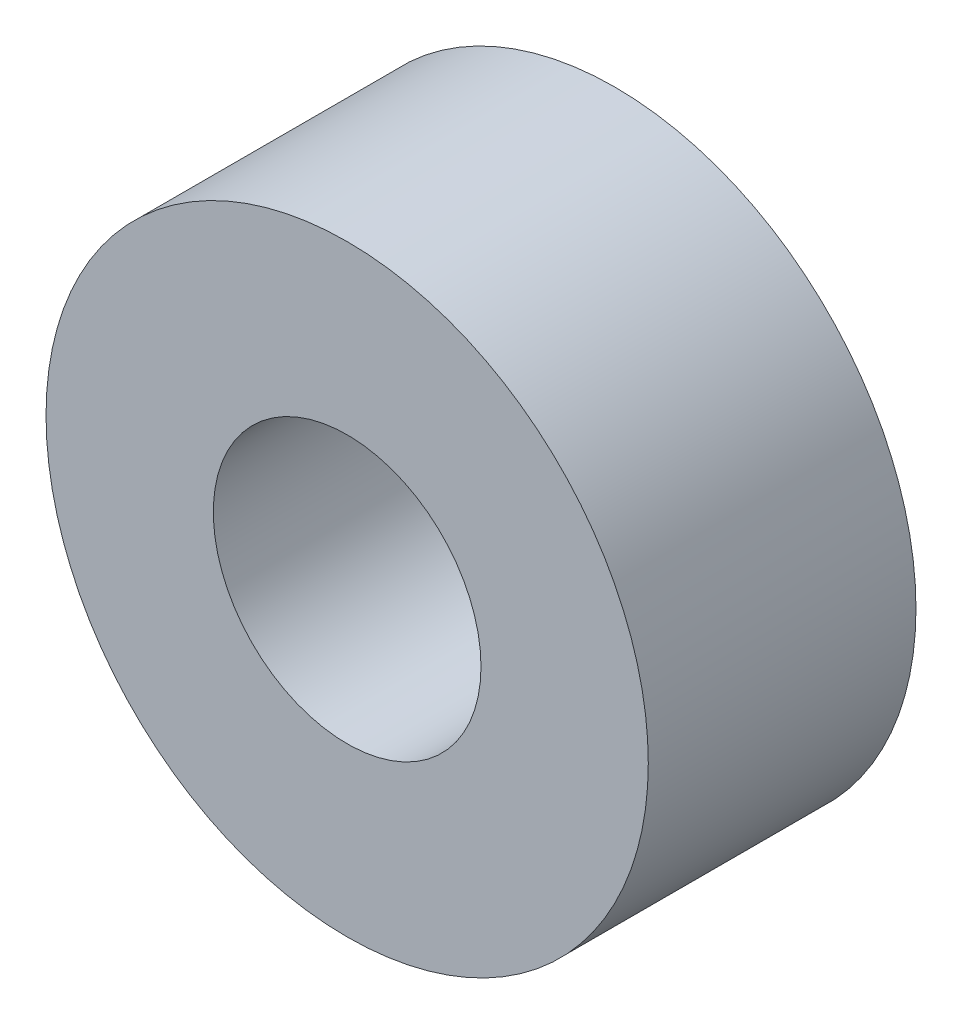
SolidWorks part; units mm, degrees
material "Liga 1060"
ref_plane "Plano frontal" through (0, 0, 0) normal (0, 0, 1) x (1, 0, 0)
ref_plane "Plano superior" through (0, 0, 0) normal (0, 1, 0) x (1, 0, 0)
ref_plane "Plano direito" through (0, 0, 0) normal (1, 0, 0) x (0, 0, -1)
sketch "Esboço1" plane through (0, 0, 0) normal (0, 0, 1) x (1, 0, 0)
  circle A0 centre (0, 0) radius 2
  circle A1 centre (0, 0) radius 4.5
  dimension "D1" = 4
  dimension "D2" = 9
extrude "Ressalto-extrusão1" add sketch "Esboço1" along normal blind 4
